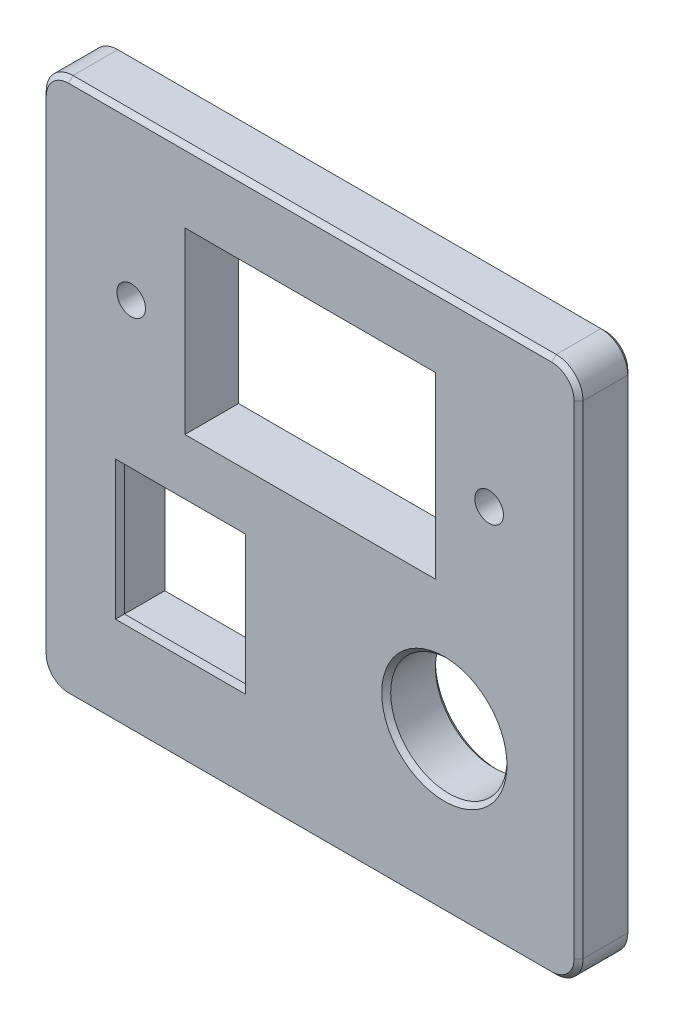
SolidWorks part; units mm, degrees
material "3D printed plastic"
ref_plane "Front Plane" through (0, 0, 0) normal (0, 0, 1) x (1, 0, 0)
ref_plane "Top Plane" through (0, 0, 0) normal (0, 1, 0) x (1, 0, 0)
ref_plane "Right Plane" through (0, 0, 0) normal (1, 0, 0) x (0, 0, -1)
sketch "Sketch1" plane through (0, 0, 0) normal (0, 0, 1) x (1, 0, 0)
  line L0 (-30, 30) -> (30, -30) construction
  line L1 (-27, 30) -> (27, 30)
  line L2 (-30, 27) -> (-30, -27)
  line L3 (-27, -30) -> (27, -30)
  line L4 (30, 27) -> (30, -27)
  arc A0 (27, 30) -> (30, 27) centre (27, 27) cw
  arc A1 (-30, -27) -> (-27, -30) centre (-27, -27) ccw
  arc A2 (27, -30) -> (30, -27) centre (27, -27) ccw
  arc A3 (-27, 30) -> (-30, 27) centre (-27, 27) ccw
  point P7 (30, 30)
  dimension "D2" = 3
  dimension "D1" = 60
extrude "Boss-Extrude1" add sketch "Sketch1" along normal blind 6
sketch "Sketch2" plane through (0, 0, 6) normal (0, 0, 1) x (1, 0, 0)
  line L0 (-14, 22) -> (14, 2) construction
  line L1 (-14, 22) -> (14, 22)
  line L2 (-14, 22) -> (-14, 2)
  line L3 (-14, 2) -> (14, 2)
  line L4 (14, 22) -> (14, 2)
  line L5 (0, 12) -> (20, 12) construction
  line L6 (0, 12) -> (-20, 12) construction
  line L7 (0, 12) -> (0, 0) construction
  line L8 (27, 30) -> (-27, 30) construction
  line L9 (30, -27) -> (30, 27) construction
  line L10 (-27, -30) -> (27, -30) construction
  circle A0 centre (-20, 12) radius 1.6
  circle A1 centre (20, 12) radius 1.6
  circle A2 centre (15, -12) radius 6.5
  point P19 (16.186, -28.5486)
  dimension "D4" = 3.2
  dimension "D6" = 13
  dimension "D1" = 20
  dimension "D2" = 28
  dimension "D3" = 40
  dimension "D5" = 18
  dimension "D7" = 15
  dimension "D8" = 18
extrude "Cut-Extrude1" cut sketch "Sketch2" against normal through all
sketch "Sketch3" plane through (0, 0, 6) normal (0, 0, 1) x (1, 0, 0)
  line L1 (-22.25, -3.75) -> (0.25, -3.75)
  line L2 (-22.25, -3.75) -> (-22.25, -20.25)
  line L3 (-22.25, -20.25) -> (0.25, -20.25)
  line L4 (0.25, -3.75) -> (0.25, -20.25)
  line L5 (-22.25, -3.75) -> (0.25, -20.25) construction
  line L6 (-11, -12) -> (15, -12) construction
  line L7 (-30, 27) -> (-30, -27) construction
  line L8 (-14, 22) -> (14, 2) construction
  line L9 (-25, 24) -> (25, 24) construction
  line L10 (-25, 24) -> (-25, 0) construction
  line L11 (-25, 0) -> (25, 0) construction
  line L12 (25, 24) -> (25, 0) construction
  line L13 (0, 12) -> (0, 24) construction
  line L14 (0, 12) -> (0, 0) construction
  circle A0 centre (15, -12) radius 9 construction
  dimension "D4" = 18
  dimension "D1" = 22.5
  dimension "D2" = 16.5
  dimension "D3" = 19
  dimension "D5" = 50
  dimension "D6" = 24
extrude "Cut-Extrude2" cut sketch "Sketch3" against normal through all from offset 1 offset against normal yes
sketch "Sketch4" plane through (0, 0, 5) normal (0, 0, -1) x (-1, 0, 0)
  line L0 (22.25, -20.25) -> (-0.25, -20.25) construction
  line L1 (22.25, -3.75) -> (7.25, -3.75) construction
  line L2 (22.25, -3.75) -> (22.25, -20.25) construction
  line L3 (22.25, -20.25) -> (7.25, -20.25) construction
  line L4 (7.25, -4.25) -> (7.25, -19.75)
  line L5 (7.25, -4.25) -> (21.75, -4.25)
  line L6 (21.75, -4.25) -> (21.75, -19.75)
  line L7 (21.75, -19.75) -> (7.25, -19.75)
  line L8 (21.75, -12) -> (22.25, -12) construction
  line L9 (7.25, -3.75) -> (7.25, -4.25) construction
  dimension "D1" = 15
  dimension "D2" = 0.5
extrude "Cut-Extrude3" cut sketch "Sketch4" against normal through all
sketch "Sketch5" plane through (0, 0, 0) normal (0, 0, 1) x (1, 0, 0)
  line L1 (-20, 8.7668) -> (-17.2, 10.3834)
  line L2 (-17.2, 10.3834) -> (-17.2, 13.6166)
  line L3 (-17.2, 13.6166) -> (-20, 15.2332)
  line L4 (-20, 15.2332) -> (-22.8, 13.6166)
  line L5 (-22.8, 13.6166) -> (-22.8, 10.3834)
  line L6 (-22.8, 10.3834) -> (-20, 8.7668)
  line L7 (20, 8.7668) -> (22.8, 10.3834)
  line L8 (22.8, 10.3834) -> (22.8, 13.6166)
  line L9 (22.8, 13.6166) -> (20, 15.2332)
  line L10 (20, 15.2332) -> (17.2, 13.6166)
  line L11 (17.2, 13.6166) -> (17.2, 10.3834)
  line L12 (17.2, 10.3834) -> (20, 8.7668)
  circle A0 centre (-20, 12) radius 2.8 construction
  circle A1 centre (20, 12) radius 2.8 construction
  dimension "D1" = 5.6
extrude "Cut-Extrude4" cut sketch "Sketch5" along normal blind 3
sketch "Sketch6" plane through (0, 0, 3) normal (0, 0, -1) x (-1, 0, 0)
  line L0 (22.8, 13.6166) -> (22.8, 10.3834) construction
  line L1 (22.8, 13.6) -> (17.2, 13.6)
  line L2 (22.8, 13.6) -> (22.8, 10.4)
  line L3 (22.8, 10.4) -> (17.2, 10.4)
  line L4 (17.2, 13.6) -> (17.2, 10.4)
  line L5 (17.2, 10.3834) -> (17.2, 13.6166) construction
  line L6 (-17.2, 13.6166) -> (-17.2, 10.3834) construction
  line L7 (-17.2, 13.6) -> (-22.8, 13.6)
  line L8 (-17.2, 13.6) -> (-17.2, 10.4)
  line L9 (-17.2, 10.4) -> (-22.8, 10.4)
  line L10 (-22.8, 13.6) -> (-22.8, 10.4)
  line L11 (-22.8, 10.3834) -> (-22.8, 13.6166) construction
  circle A0 centre (-20, 12) radius 1.6 construction
  circle A1 centre (20, 12) radius 1.6 construction
extrude "Cut-Extrude5" cut sketch "Sketch6" against normal blind 0.4
sketch "Sketch7" plane through (0, 0, 0) normal (0, 0, -1) x (-1, 0, 0)
  line L0 (-26, -26) -> (-26, 26) construction
  line L1 (-26, 26) -> (26, 26) construction
  line L2 (26, 26) -> (26, -26) construction
  line L3 (26, -26) -> (-26, -26) construction
  line L4 (-26, -26) -> (26, 26) construction
  circle A0 centre (-26, 26) radius 1.3
  circle A1 centre (26, 26) radius 1.3
  circle A2 centre (26, -26) radius 1.3
  circle A3 centre (-26, -26) radius 1.3
  dimension "D1" = 52
  dimension "D2" = 2.6
extrude "Cut-Extrude6" cut sketch "Sketch7" against normal offset from surface (5 mm away) 1 up to face at (-14.5, -12, 6)
chamfer "Chamfer2" distance 0.5 angle 45 22 edges at (24.7, -26, 0) (-27.3, -26, 0) (-27.3, 26, 0) (24.7, 26, 0) (30, 0, 0) (29.1213, 29.1213, 0) (29.1213, -29.1213, 0) (0, 30, 0) (0, -30, 0) (-29.1213, 29.1213, 0) (-29.1213, -29.1213, 0) (-30, 0, 0) (21.5, -12, 6) (21.5, -12, 0) (30, 0, 6) (29.1213, 29.1213, 6) (29.1213, -29.1213, 6) (0, 30, 6) (0, -30, 6) (-29.1213, 29.1213, 6) (-29.1213, -29.1213, 6) (-30, 0, 6)
